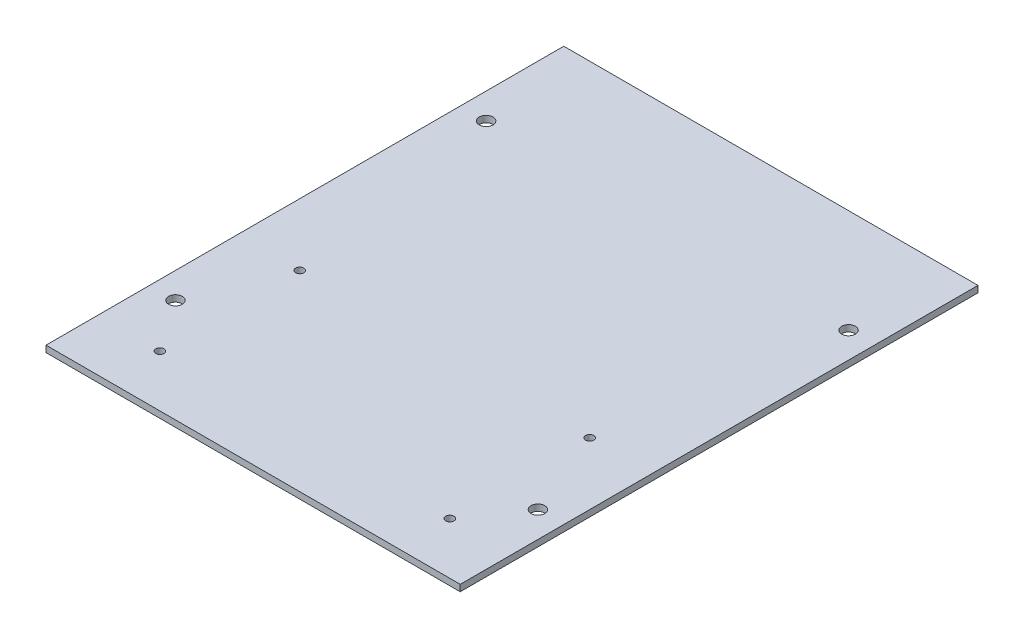
SolidWorks part; units mm, degrees
ref_plane "Front Plane" through (0, 0, 0) normal (0, 0, 1) x (1, 0, 0)
ref_plane "Top Plane" through (0, 0, 0) normal (0, 1, 0) x (1, 0, 0)
ref_plane "Right Plane" through (0, 0, 0) normal (1, 0, 0) x (0, 0, -1)
sketch "Sketch1" plane through (0, 0, 0) normal (0, 1, 0) x (1, 0, 0)
  line L1 (0, 0) -> (203.2, 0)
  line L2 (0, 0) -> (0, 254)
  line L3 (0, 254) -> (203.2, 254)
  line L4 (203.2, 0) -> (203.2, 254)
  dimension "D1" = 203.2
  dimension "D2" = 254
extrude "Boss-Extrude1" add sketch "Sketch1" along normal blind 3.175
sketch "Sketch2" plane through (0, 3.175, 0) normal (0, 1, 0) x (1, 0, 0)
  line L0 (12.7, 0) -> (12.7, 254) construction
  line L1 (0, 0) -> (203.2, 0) construction
  line L2 (203.2, 254) -> (0, 254) construction
  line L3 (12.7, 254) -> (190.5, 254) construction
  line L4 (190.5, 254) -> (190.5, 0) construction
  line L5 (203.2, 0) -> (203.2, 254) construction
  line L6 (0, 254) -> (0, 0) construction
  line L7 (0, 203.2) -> (203.2, 203.2) construction
  line L8 (0, 50.8) -> (203.2, 50.8) construction
  circle A0 centre (190.5, 203.2) radius 3.3734
  circle A1 centre (12.7, 203.2) radius 3.3734
  circle A2 centre (12.7, 50.8) radius 3.3734
  circle A3 centre (190.5, 50.8) radius 3.3734
  point P24 (0, 204.2267)
  point P25 (0, 203.8149)
  point P26 (12.7, 203.2)
  point P27 (12.7, 50.8)
  point P28 (190.5, 50.8)
  point P29 (190.5, 203.2)
  dimension "D5" = 6.7469
  dimension "D1" = 12.7
  dimension "D2" = 12.7
  dimension "D3" = 50.8
  dimension "D4" = 50.8
extrude "Cut-Extrude1" cut sketch "Sketch2" against normal through all
sketch "Sketch3" plane through (0, 3.175, 0) normal (0, 1, 0) x (1, 0, 0)
  line L0 (30.48, 25.4) -> (172.72, 25.4) construction
  line L1 (172.72, 25.4) -> (172.72, 93.98) construction
  line L2 (172.72, 93.98) -> (30.48, 93.98) construction
  line L3 (30.48, 93.98) -> (30.48, 25.4) construction
  line L4 (0, 0) -> (203.2, 0) construction
  line L5 (0, 254) -> (0, 0) construction
  line L6 (203.2, 0) -> (203.2, 254) construction
  circle A0 centre (172.72, 93.98) radius 2.5797
  circle A1 centre (172.72, 25.4) radius 2.5797
  circle A2 centre (30.48, 93.98) radius 2.5797
  circle A3 centre (30.48, 25.4) radius 2.5797
  point P14 (0, 0)
  dimension "D1" = 5.1594
  dimension "D2" = 30.48
  dimension "D3" = 25.4
  dimension "D4" = 142.24
  dimension "D5" = 68.58
hole_wizard "#10-32 Tapped Hole1" positions "Sketch4" profile "Sketch5" tap size "#10-32" standard "ANSI Inch" end condition through all
sketch "Sketch4" plane through (0, 3.175, 0) normal (0, 1, 0) x (1, 0, 0)
  point P0 (172.72, 25.4)
  point P3 (172.72, 93.98)
  point P6 (30.48, 25.4)
  point P9 (30.48, 93.98)
sketch "Sketch5" plane through (172.72, 3.175, -25.4) normal (1, 0, 0) x (0, 0, 1)
  line L0 (0, 0) -> (0, 3.175)
  line L1 (0, 3.175) -> (2.0193, 3.175)
  line L2 (2.0193, 3.175) -> (2.0193, 0)
  line L5 (2.0193, 0) -> (0, 0)
  line L11 (0, -6.35) -> (0, 107.95) construction
  dimension "Thru Tap Drill Dia." = 4.0386
  dimension "Thru Tap Drill Depth" = 3.175
cosmetic thread "Hole Thread1" parameters "D2"=4.826
cosmetic thread "Hole Thread2" parameters "D2"=4.826
cosmetic thread "Hole Thread3" parameters "D2"=4.826
cosmetic thread "Hole Thread4" parameters "D2"=4.826
